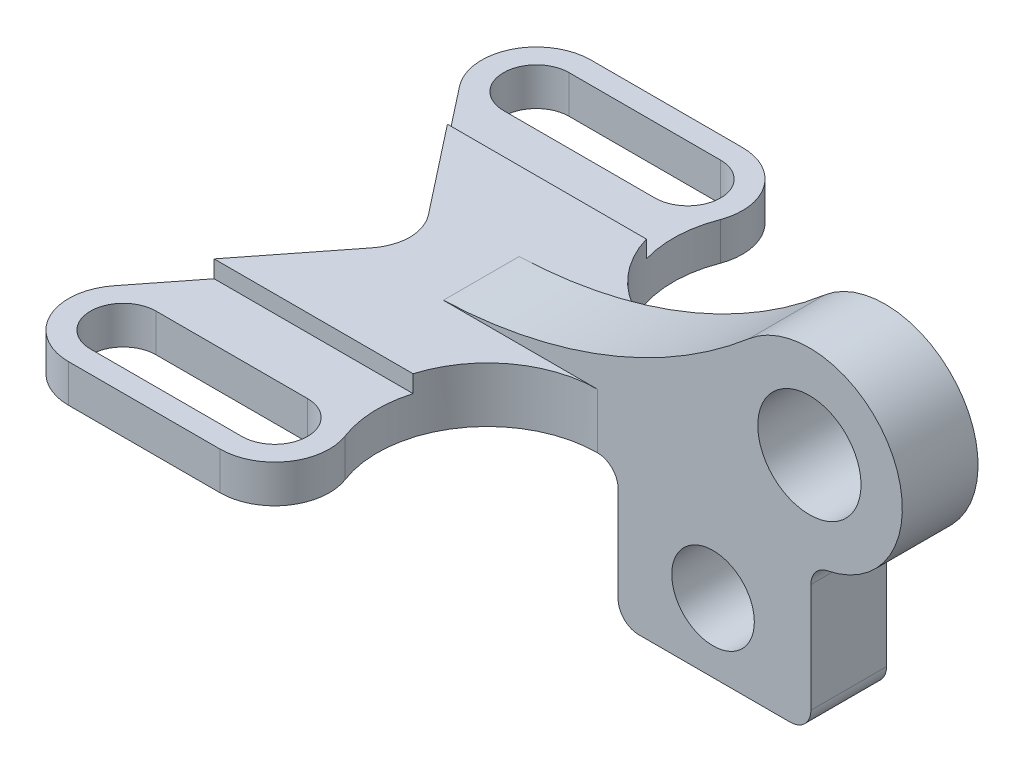
SolidWorks part; units mm, degrees
ref_plane "Front Plane" through (0, 0, 0) normal (0, 0, 1) x (1, 0, 0)
ref_plane "Top Plane" through (0, 0, 0) normal (0, 1, 0) x (1, 0, 0)
ref_plane "Right Plane" through (0, 0, 0) normal (1, 0, 0) x (0, 0, -1)
sketch "Sketch1" plane through (0, 0, 0) normal (0, 0, 1) x (1, 0, 0)
  line L1 (55.6044, -9.4062) -> (55.6044, -41.0382)
  line L4 (-6.3956, -7.2574) -> (-51.1629, -7.2574)
  line L5 (55.1767, 22.9618) -> (55.1767, -7.0382)
  line L8 (49.6044, -47.0382) -> (5.6044, -47.0382)
  line L9 (-51.1629, -7.2574) -> (-51.1629, 8.7426)
  line L10 (-0.3956, -13.2574) -> (-0.3956, -41.0382)
  line L12 (-6.3956, -7.2574) -> (-6.3956, 8.7426)
  circle A0 centre (55.1767, 22.9618) radius 15
  circle A1 centre (27.1767, -27.0382) radius 12
  arc A4 (55.6044, -41.0382) -> (49.6044, -47.0382) centre (49.6044, -41.0382) cw
  arc A6 (37.6208, 43.475) -> (60.4357, -3.5211) centre (55.1767, 22.9618) cw
  arc A7 (60.4357, -3.5211) -> (55.6044, -9.4062) centre (61.6044, -9.4062) ccw
  arc A10 (-0.3956, -41.0382) -> (5.6044, -47.0382) centre (5.6044, -41.0382) ccw
  arc A11 (-0.3956, -13.2574) -> (-6.3956, -7.2574) centre (-6.3956, -13.2574) ccw
  arc A13 (-51.1629, 8.7426) -> (37.6208, 43.475) centre (-56.6609, 153.6383) ccw
  point P16 (0, 0)
  point P20 (27.6044, -47.0382)
  point P22 (27.6044, -47.0382)
  point P24 (-2.1704, 0.2969)
extrude "Boss-Extrude1" add sketch "Sketch1" along normal blind 22
ref_plane "Plane2" through (0, -7.2574, 0) normal (0, -1, 0) x (-1, 0, 0)
sketch "Sketch7" plane through (0, -7.2574, 0) normal (0, -1, 0) x (1, 0, 0)
  line L1 (-74.8422, 2.6635) -> (-107.6657, -39.1961)
  line L2 (-51.1629, -39.4638) -> (-95.1629, -39.4638)
  line L3 (-51.1629, -64.8883) -> (-95.1629, -64.8883)
  line L4 (-51.1629, -58.5362) -> (-95.1629, -58.5362)
  line L5 (-0.3956, 22) -> (-6.3956, 22) construction
  line L6 (-51.1629, 80.5362) -> (-95.1629, 80.5362)
  line L7 (-51.1629, 86.8883) -> (-95.1629, 86.8883)
  line L8 (-51.1629, 61.4638) -> (-95.1629, 61.4638)
  line L11 (-74.8422, 19.3365) -> (-107.6657, 61.1961)
  line L12 (-6.3956, 0) -> (-0.3956, 0) construction
  arc A2 (-51.1629, 80.5362) -> (-51.1629, 61.4638) centre (-51.1629, 71) cw
  arc A3 (-36.2405, 65.5449) -> (-51.1629, 86.8883) centre (-51.1629, 71) ccw
  arc A4 (-6.3956, 22) -> (-36.2405, 65.5449) centre (-6.3956, 54) cw
  arc A5 (-95.1629, 80.5362) -> (-95.1629, 61.4638) centre (-95.1629, 71) ccw
  arc A8 (-95.1629, 86.8883) -> (-107.6657, 61.1961) centre (-95.1629, 71) ccw
  arc A9 (-71.8799, 11) -> (-74.8422, 19.3365) centre (-85.7905, 10.7516) ccw
  arc A10 (-71.8799, 11) -> (-74.8422, 2.6635) centre (-85.7905, 11.2484) cw
  arc A11 (-95.1629, -64.8883) -> (-107.6657, -39.1961) centre (-95.1629, -49) cw
  arc A12 (-95.1629, -58.5362) -> (-95.1629, -39.4638) centre (-95.1629, -49) cw
  arc A13 (-6.3956, 0) -> (-36.2405, -43.5449) centre (-6.3956, -32) ccw
  arc A14 (-36.2405, -43.5449) -> (-51.1629, -64.8883) centre (-51.1629, -49) cw
  arc A15 (-51.1629, -58.5362) -> (-51.1629, -39.4638) centre (-51.1629, -49) ccw
  point P17 (-73.1629, 80.5362)
  point P20 (-73.1629, 61.4638)
  point P35 (-73.1629, -39.4638)
  point P36 (-73.1629, -58.5362)
  line M9 (-51.1629, 0) -> (-6.3956, 0)
  line M11 (-6.3956, 22) -> (-51.1629, 22)
  line M12 (-51.1629, 22) -> (-51.1629, 0)
extrude "Boss-Extrude3" add sketch "Sketch7" against normal blind 16 contours A14 A13 A4 A3 L7 A8 L11 A9 A10 L1 A11 L3 A15 L4 A12 L2 A5 L6 A2 L8 M9 M12 M11
sketch "Sketch9" plane through (0, 0, 86.8883) normal (0, 0, 1) x (1, 0, 0)
  line L0 (-111.0512, 8.7426) -> (-35.2746, 8.7426)
  line L1 (-35.2746, 8.7426) -> (-35.2746, 3.7426)
  line L2 (-35.2746, -7.2574) -> (-35.2746, 8.7426) construction
  line L3 (-35.2746, 3.7426) -> (-111.0512, 3.7426)
  line L4 (-111.0512, 8.7426) -> (-111.0512, -7.2574) construction
  line L5 (-111.0512, 3.7426) -> (-111.0512, 8.7426)
extrude "Cut-Extrude1" cut sketch "Sketch9" against normal blind 42
sketch "Sketch10" plane through (0, 0, -64.8883) normal (0, 0, -1) x (-1, 0, 0)
  line L0 (111.0512, 8.7426) -> (35.2746, 8.7426)
  line L1 (35.2746, 8.7426) -> (35.2746, 3.7426)
  line L2 (35.2746, 8.7426) -> (35.2746, -7.2574) construction
  line L3 (35.2746, 3.7426) -> (111.0512, 3.7426)
  line L4 (111.0512, -7.2574) -> (111.0512, 8.7426) construction
  line L5 (111.0512, 3.7426) -> (111.0512, 8.7426)
extrude "Cut-Extrude2" cut sketch "Sketch10" against normal blind 42
